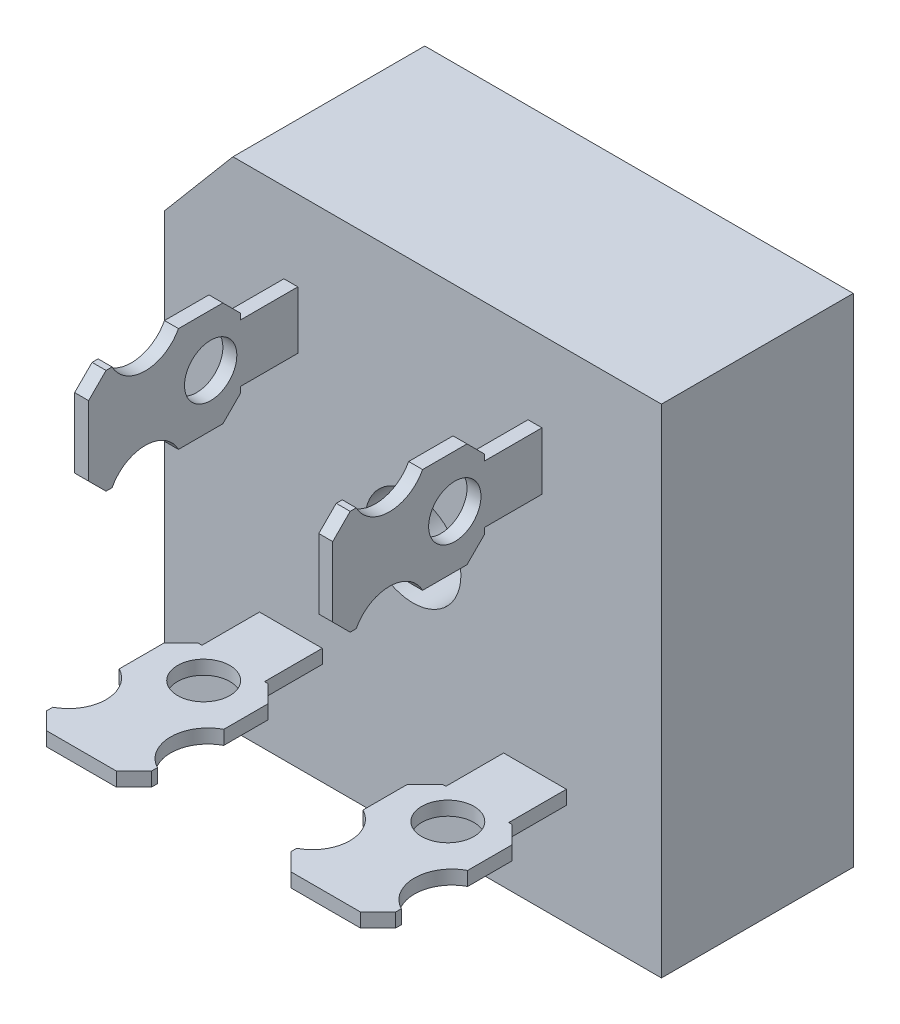
SolidWorks part; units mm, degrees
ref_plane "Спереди" through (0, 0, 0) normal (0, 0, 1) x (1, 0, 0)
ref_plane "Сверху" through (0, 0, 0) normal (0, 1, 0) x (1, 0, 0)
ref_plane "Справа" through (0, 0, 0) normal (1, 0, 0) x (0, 0, -1)
sketch "Эскиз1" plane through (0, 0, 0) normal (0, 0, 1) x (1, 0, 0)
  line L0 (-13.4355, 14.25) -> (44.3515, 14.25) construction
  line L1 (0, 0) -> (28.5, 0)
  line L2 (0, 0) -> (0, 28.5)
  line L3 (0, 28.5) -> (28.5, 28.5)
  line L4 (28.5, 0) -> (28.5, 28.5)
  line L5 (14.25, 40.3064) -> (14.25, -19.792) construction
  circle A0 centre (14.25, 14.25) radius 2.75
  dimension "D2" = 5.5
  dimension "D1" = 28.5
extrude "Вытянуть1" add sketch "Эскиз1" along normal blind 11
sketch "Эскиз2" plane through (0, 0, 11) normal (0, 0, 1) x (1, 0, 0)
  line L0 (-3.778, 14.25) -> (33.1934, 14.25) construction
  line L1 (14.25, 31.8711) -> (14.25, 3.8502) construction
  line L2 (0, 28.5) -> (0, 0) construction
  line L3 (28.5, 0) -> (28.5, 28.5) construction
  line L4 (28.5, 28.5) -> (0, 28.5) construction
  line L5 (0, 0) -> (28.5, 0) construction
  line L6 (-2.6083, 6.25) -> (31.2609, 6.25) construction
  line L7 (-4.3374, 22.25) -> (30.8541, 22.25) construction
  line L8 (7.25, 31.3791) -> (7.25, -1.1663) construction
  line L9 (4.25, 5.85) -> (10.25, 5.85)
  line L10 (4.25, 5.85) -> (4.25, 6.65)
  line L11 (4.25, 6.65) -> (10.25, 6.65)
  line L12 (10.25, 5.85) -> (10.25, 6.65)
  line L13 (24.25, 5.85) -> (18.25, 5.85)
  line L14 (24.25, 5.85) -> (24.25, 6.65)
  line L15 (24.25, 6.65) -> (18.25, 6.65)
  line L16 (18.25, 5.85) -> (18.25, 6.65)
  line L17 (21.65, 19.25) -> (20.85, 19.25)
  line L18 (21.65, 19.25) -> (21.65, 25.25)
  line L19 (21.65, 25.25) -> (20.85, 25.25)
  line L20 (20.85, 19.25) -> (20.85, 25.25)
  line L21 (6.85, 19.25) -> (7.65, 19.25)
  line L22 (6.85, 19.25) -> (6.85, 25.25)
  line L23 (6.85, 25.25) -> (7.65, 25.25)
  line L24 (7.65, 19.25) -> (7.65, 25.25)
  line L25 (21.25, 31.8711) -> (21.25, 0) construction
  dimension "D1" = 8
  dimension "D2" = 8
  dimension "D3" = 7
  dimension "D4" = 7
  dimension "D5" = 6
  dimension "D6" = 0.8
extrude "Вытянуть2" add sketch "Эскиз2" along normal blind 12
sketch "Эскиз3" plane through (0, 5.85, 0) normal (0, -1, 0) x (1, 0, 0)
  line L0 (2.3311, 16) -> (25.8269, 16) construction
  line L1 (7.25, 24.2739) -> (7.25, 9.5335) construction
  line L2 (21.25, 25.1289) -> (21.25, 7.1725) construction
  line L3 (18.25, 23) -> (18.25, 11) construction
  line L4 (24.25, 23) -> (24.25, 11) construction
  line L5 (4.25, 23) -> (4.25, 11) construction
  line L6 (10.25, 23) -> (10.25, 11) construction
  line L7 (0, 11) -> (28.5, 11) construction
  line L8 (3.25, 19.75) -> (29.1027, 19.75) construction
  line L9 (4.25, 11) -> (5.45, 11)
  line L10 (4.25, 11) -> (4.25, 14.3)
  line L11 (4.25, 14.3) -> (5.45, 14.3)
  line L12 (5.45, 11) -> (5.45, 14.3)
  line L13 (10.25, 11) -> (9.05, 11)
  line L14 (10.25, 11) -> (10.25, 14.3091)
  line L15 (10.25, 14.3091) -> (9.05, 14.3091)
  line L16 (9.05, 11) -> (9.05, 14.3091)
  line L17 (18.25, 11) -> (19.45, 11)
  line L18 (18.25, 11) -> (18.25, 14.3091)
  line L19 (18.25, 14.3091) -> (19.45, 14.3091)
  line L20 (19.45, 11) -> (19.45, 14.3091)
  line L21 (24.25, 11) -> (23.05, 11)
  line L22 (24.25, 11) -> (24.25, 14.3091)
  line L23 (24.25, 14.3091) -> (23.05, 14.3091)
  line L24 (23.05, 11) -> (23.05, 14.3091)
  line L25 (28.5, 11) -> (0, 11) construction
  circle A0 centre (7.25, 16) radius 1.5
  circle A1 centre (21.25, 16) radius 1.5
  circle A2 centre (3.25, 19.75) radius 2.15
  circle A3 centre (11.25, 19.75) radius 2.15
  circle A4 centre (17.25, 19.7646) radius 2.15
  circle A5 centre (25.25, 19.7646) radius 2.15
  dimension "D2" = 3
  dimension "D3" = 8
  dimension "D4" = 8
  dimension "D5" = 8.75
  dimension "D6" = 4.3
  dimension "D1" = 5
  dimension "D7" = 3.3
  dimension "D8" = 3.6
extrude "Вырез-Вытянуть1" cut sketch "Эскиз3" against normal blind 2
sketch "Эскиз4" plane through (6.85, 0, 0) normal (-1, 0, 0) x (0, 0, 1)
  line L0 (16, 27.4086) -> (16, 3.4222) construction
  line L1 (11, 28.5) -> (11, 0) construction
  line L2 (8.9785, 22.25) -> (24.4891, 22.25) construction
  line L3 (23, 19.25) -> (11, 19.25) construction
  line L4 (23, 25.25) -> (11, 25.25) construction
  line L5 (19.75, 6.65) -> (19.75, 5.85) construction
  line L6 (11, 25.25) -> (14.3, 25.25)
  line L7 (11, 25.25) -> (11, 23.9)
  line L8 (11, 23.9) -> (14.3, 23.9)
  line L9 (14.3, 25.25) -> (14.3, 23.9)
  line L10 (11, 19.25) -> (14.3, 19.25)
  line L11 (11, 19.25) -> (11, 20.6)
  line L12 (11, 20.6) -> (14.3, 20.6)
  line L13 (14.3, 19.25) -> (14.3, 20.6)
  line L15 (14.3, 6.65) -> (14.3, 5.85) construction
  line L16 (19.75, 26.25) -> (19.75, 11.4249) construction
  circle A0 centre (16, 22.25) radius 1.5
  circle A1 centre (19.75, 18.25) radius 2.15
  circle A2 centre (19.75, 26.25) radius 2.15
  dimension "D2" = 3
  dimension "D3" = 8
  dimension "D5" = 4.3
  dimension "D1" = 5
  dimension "D4" = 3.3
extrude "Вырез-Вытянуть2" cut sketch "Эскиз4" against normal blind 20
chamfer "Фаска1" distance 1 angle 45
sketch "Эскиз5" plane through (0, 0, 11) normal (0, 0, 1) x (1, 0, 0)
  line L0 (28.5, 28.5) -> (0, 28.5) construction
  line L3 (3.9274, 28.5) -> (0, 28.5)
  line L4 (0, 28.5) -> (0, 0) construction
  line L5 (0, 28.5) -> (0, 23.8502)
  line L6 (3.9274, 28.5) -> (0, 23.8502)
extrude "Вырез-Вытянуть3" cut sketch "Эскиз5" against normal blind 15
